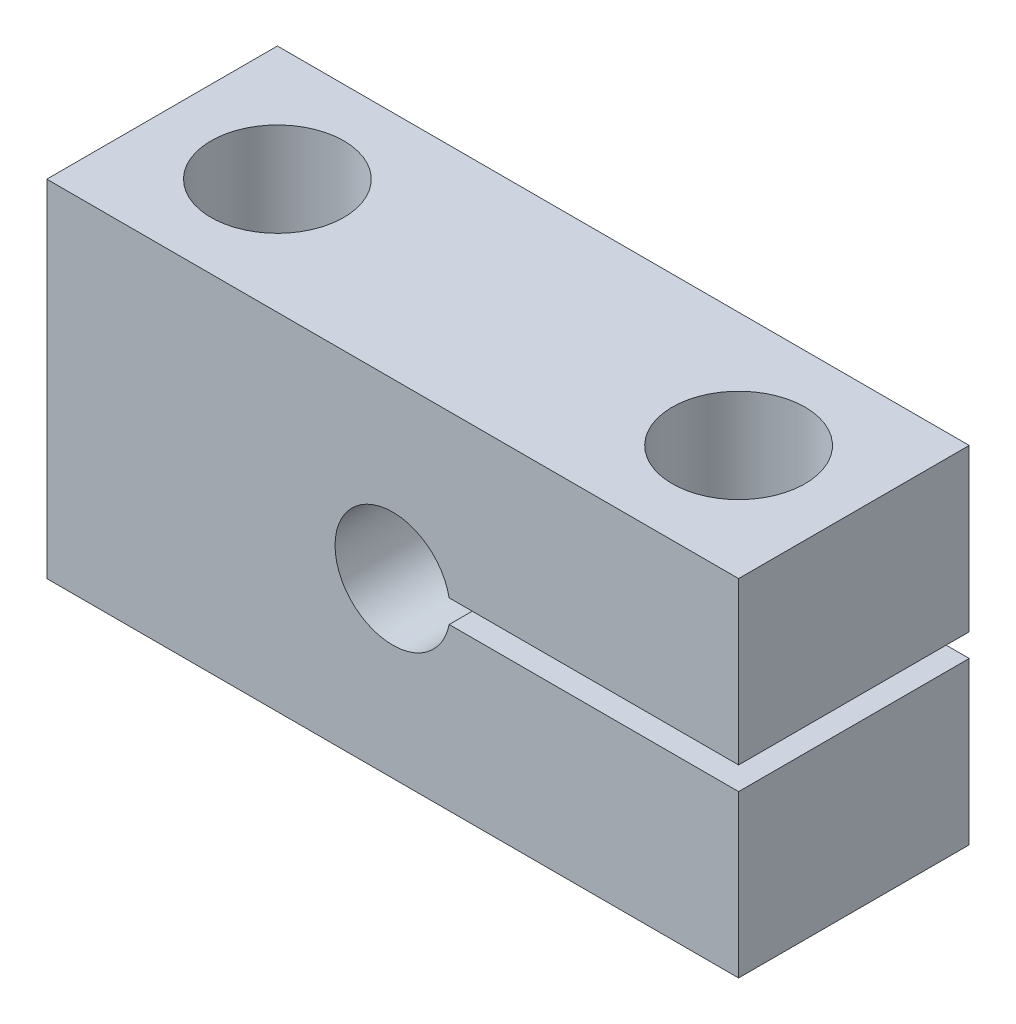
SolidWorks part; units mm, degrees
material "6061-T6 (SS)"
ref_plane "Front Plane" through (0, 0, 0) normal (0, 0, 1) x (1, 0, 0)
ref_plane "Top Plane" through (0, 0, 0) normal (0, 1, 0) x (1, 0, 0)
ref_plane "Right Plane" through (0, 0, 0) normal (1, 0, 0) x (0, 0, -1)
sketch "Sketch1" plane through (0, 0, 0) normal (0, 0, 1) x (1, 0, 0)
  line L0 (0, 0) -> (0, 4.7625) construction
  line L1 (-9.525, -4.7625) -> (9.525, -4.7625)
  line L2 (-9.525, -4.7625) -> (-9.525, 4.7625)
  line L3 (-9.525, 4.7625) -> (9.525, 4.7625)
  line L4 (9.525, -4.7625) -> (9.525, -0.3175)
  line L5 (1.5554, 0.3175) -> (9.525, 0.3175)
  line L6 (1.5554, -0.3175) -> (9.525, -0.3175)
  line L7 (9.525, 0.3175) -> (9.525, 4.7625)
  line L8 (1.5554, 0.3175) -> (1.5554, -0.3175) construction
  line L9 (1.5554, 0) -> (0, 0) construction
  arc A0 (1.5554, 0.3175) -> (1.5554, -0.3175) centre (0, 0) ccw
  dimension "D1" = 3.175
  dimension "D2" = 4.7625
  dimension "D3" = 4.7625
  dimension "D4" = 19.05
  dimension "D5" = 0.635
extrude "Boss-Extrude1" add sketch "Sketch1" along normal blind 6.35
sketch "Sketch2" plane through (0, -4.7625, 0) normal (0, -1, 0) x (1, 0, 0)
  line L0 (-9.525, 3.175) -> (-6.35, 3.175) construction
  line L1 (-9.525, 6.35) -> (-9.525, 0) construction
  line L2 (-6.35, 3.175) -> (6.35, 3.175) construction
  line L3 (0, 3.175) -> (0, 0) construction
  circle A0 centre (-6.35, 3.175) radius 1.8288
  circle A1 centre (6.35, 3.175) radius 1.8288
  dimension "D1" = 3.6576
  dimension "D2" = 12.7
extrude "Cut-Extrude1" cut sketch "Sketch2" against normal through all
